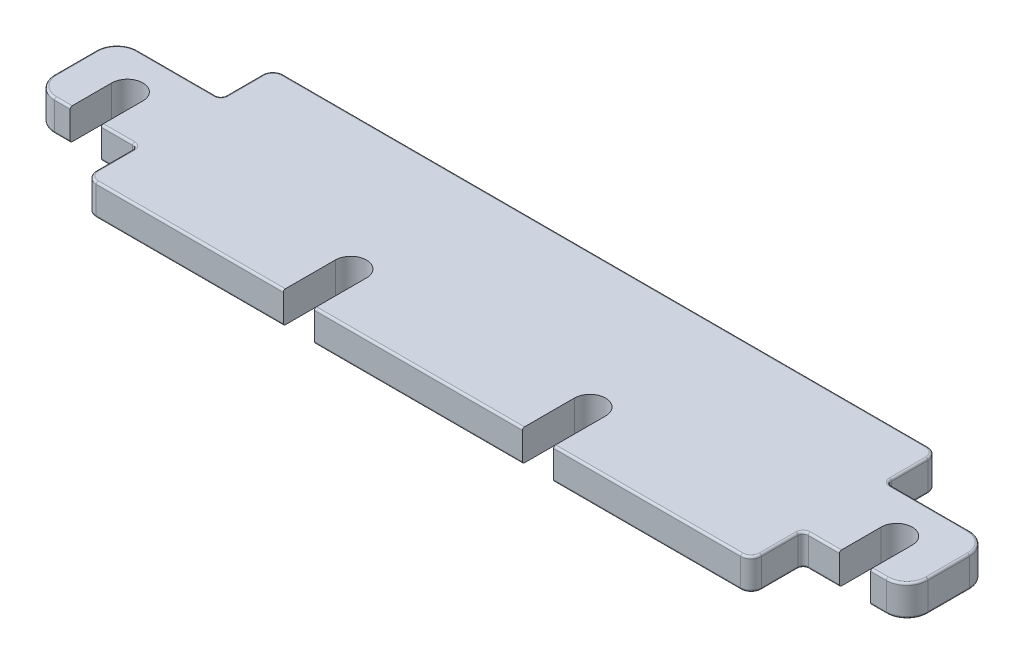
SolidWorks part; units mm, degrees
ref_plane "Front Plane" through (0, 0, 0) normal (0, 0, 1) x (1, 0, 0)
ref_plane "Top Plane" through (0, 0, 0) normal (0, 1, 0) x (1, 0, 0)
ref_plane "Right Plane" through (0, 0, 0) normal (1, 0, 0) x (0, 0, -1)
sketch "Sketch1" plane through (0, 0, 0) normal (0, 1, 0) x (1, 0, 0)
  line L0 (0, 0) -> (0, 18) construction
  line L1 (-10, 5) -> (-10, 0)
  line L2 (-10, 0) -> (10, 0)
  line L3 (-13, 5) -> (-13, 0)
  line L4 (-13, 0) -> (-31, 0)
  line L5 (-32, 1) -> (-32, 4.5)
  line L6 (-32.5, 5) -> (-35.5, 5)
  line L7 (-42, 7) -> (-42, 11)
  line L8 (-40, 13) -> (-32.5, 13)
  line L9 (-32, 13.5) -> (-32, 17)
  line L10 (-31, 18) -> (31, 18)
  line L11 (-38.5, 9) -> (-38.5, 5)
  line L12 (-35.5, 9) -> (-35.5, 5)
  line L13 (-38.5, 5) -> (-40, 5)
  line L14 (38.5, 5) -> (40, 5)
  line L15 (35.5, 9) -> (35.5, 5)
  line L16 (38.5, 9) -> (38.5, 5)
  line L17 (32, 13.5) -> (32, 17)
  line L18 (40, 13) -> (32.5, 13)
  line L19 (42, 7) -> (42, 11)
  line L20 (32.5, 5) -> (35.5, 5)
  line L21 (32, 1) -> (32, 4.5)
  line L22 (13, 0) -> (31, 0)
  line L23 (13, 5) -> (13, 0)
  line L24 (10, 5) -> (10, 0)
  arc A0 (-10, 5) -> (-13, 5) centre (-11.5, 5) ccw
  arc A1 (-35.5, 9) -> (-38.5, 9) centre (-37, 9) ccw
  arc A2 (-31, 0) -> (-32, 1) centre (-31, 1) cw
  arc A3 (-32, 17) -> (-31, 18) centre (-31, 17) cw
  arc A4 (-40, 5) -> (-42, 7) centre (-40, 7) cw
  arc A5 (-42, 11) -> (-40, 13) centre (-40, 11) cw
  arc A6 (-32, 4.5) -> (-32.5, 5) centre (-32.5, 4.5) ccw
  arc A7 (-32.5, 13) -> (-32, 13.5) centre (-32.5, 13.5) ccw
  arc A8 (32.5, 13) -> (32, 13.5) centre (32.5, 13.5) cw
  arc A9 (32, 4.5) -> (32.5, 5) centre (32.5, 4.5) cw
  arc A10 (42, 11) -> (40, 13) centre (40, 11) ccw
  arc A11 (40, 5) -> (42, 7) centre (40, 7) ccw
  arc A12 (32, 17) -> (31, 18) centre (31, 17) ccw
  arc A13 (31, 0) -> (32, 1) centre (31, 1) ccw
  arc A14 (35.5, 9) -> (38.5, 9) centre (37, 9) cw
  arc A15 (10, 5) -> (13, 5) centre (11.5, 5) cw
  point P21 (-32, 0)
  point P26 (-42, 5)
  point P29 (-42, 13)
  point P32 (-32, 5)
  point P63 (32, 5)
  point P64 (42, 13)
  point P65 (42, 5)
  point P66 (32, 0)
  dimension "D1" = 3
  dimension "D9" = 3
  dimension "D12" = 1
  dimension "D13" = 2
  dimension "D14" = 0.5
  dimension "D2" = 10
  dimension "D3" = 5
  dimension "D4" = 32
  dimension "D5" = 10
  dimension "D6" = 8
  dimension "D7" = 18
  dimension "D8" = 5
  dimension "D10" = 5
  dimension "D11" = 4
extrude "Boss-Extrude1" add sketch "Sketch1" along normal blind 3
fillet "Fillet1" radius 0.2 56 edges at (22, 3, 0) (31.7071, 3, -0.2929) (34, 3, -5) (32.1464, 3, -4.8536) (34, 0, -5) (32.1464, 0, -4.8536) (32, 0, -2.75) (31.7071, 0, -0.2929) (39.25, 0, -5) (41.4142, 0, -5.5858) (42, 0, -9) (41.4142, 0, -12.4142) (36.25, 0, -13) (32.1464, 0, -13.1464) (32, 0, -15.25) (31.7071, 0, -17.7071) (0, 0, -18) (-31.7071, 0, -17.7071) (-32, 0, -15.25) (-32.1464, 0, -13.1464) (-36.25, 0, -13) (-41.4142, 0, -12.4142) (-42, 0, -9) (-41.4142, 0, -5.5858) (-34, 0, -5) (-32.1464, 0, -4.8536) (-32, 0, -2.75) (-31.7071, 0, -0.2929) (39.25, 3, -5) (41.4142, 3, -5.5858) (42, 3, -9) (41.4142, 3, -12.4142) (36.25, 3, -13) (32.1464, 3, -13.1464) (32, 3, -15.25) (31.7071, 3, -17.7071) (0, 3, -18) (-31.7071, 3, -17.7071) (-32, 3, -15.25) (-32.1464, 3, -13.1464) (-36.25, 3, -13) (-41.4142, 3, -12.4142) (-42, 3, -9) (-41.4142, 3, -5.5858) (-34, 3, -5) (-32.1464, 3, -4.8536) (-32, 3, -2.75) (-31.7071, 3, -0.2929) (32, 3, -2.75) (22, 0, 0) (-39.25, 0, -5) (-22, 0, 0) (0, 0, 0) (0, 3, 0) (-39.25, 3, -5) (-22, 3, 0)
ref_plane "Plane1" through (0, 0, -5) normal (0, 0, 1) x (0, -1, 0)
ref_plane "Plane2" through (0, 0, -9) normal (0, 0, 1) x (0, -1, 0)
